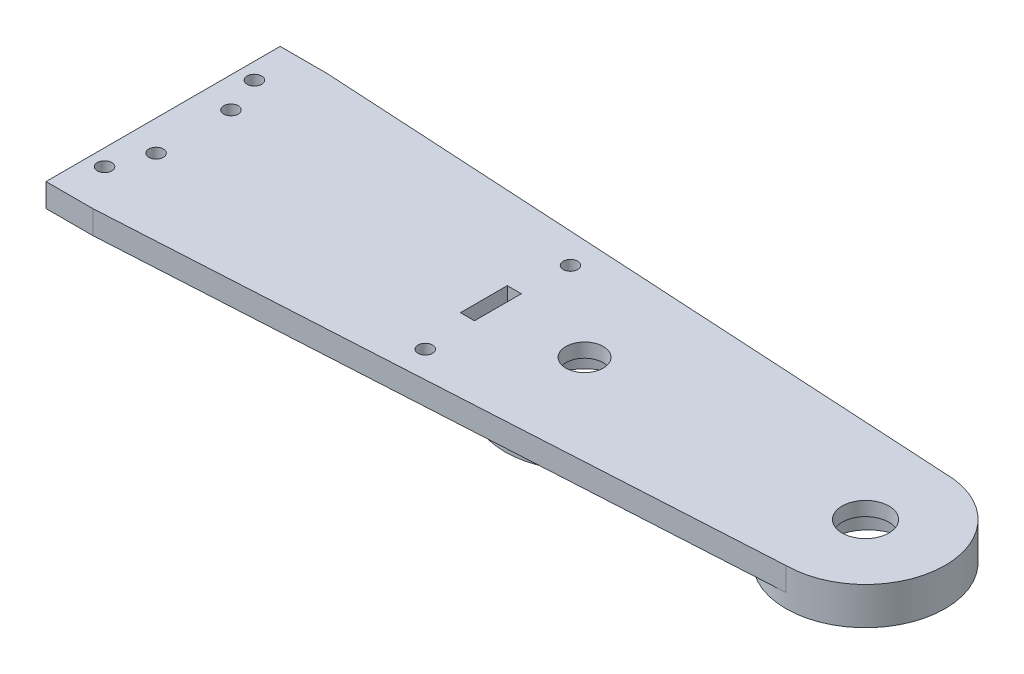
SolidWorks part; units mm, degrees
ref_plane "Front Plane" through (0, 0, 0) normal (0, 0, 1) x (1, 0, 0)
ref_plane "Top Plane" through (0, 0, 0) normal (0, 1, 0) x (1, 0, 0)
ref_plane "Right Plane" through (0, 0, 0) normal (1, 0, 0) x (0, 0, -1)
sketch "Sketch28" plane through (-32, 0, 0) normal (0, -1, 0) x (0, 0, 1)
  line L1 (0, -75) -> (0, -135) construction
  line L2 (-8, 8.5) -> (8, 8.5) construction
  line L3 (0, -75) -> (0, 15) construction
  line L8 (-25, 15) -> (25, 15)
  line L12 (25, 15) -> (25, 5)
  line L13 (-25, 15) -> (-25, 5)
  line L14 (-25, 5) -> (-17, -135)
  line L15 (17, -135) -> (25, 5)
  line L16 (-25, 5) -> (-25, 8.5) construction
  line L17 (-25, 8.5) -> (-8, 8.5) construction
  line L18 (-25, 15) -> (-25, 11.5) construction
  line L19 (-25, 11.5) -> (-16, 11.5) construction
  line L20 (-16, 11.5) -> (16, 11.5) construction
  line L21 (0, -75) -> (0, -56.5) construction
  line L22 (5, -56.5) -> (-5, -56.5)
  line L23 (-5, -56.5) -> (-5, -53.5)
  line L24 (-5, -53.5) -> (5, -53.5)
  line L25 (5, -53.5) -> (5, -56.5)
  line L26 (-5, -53.5) -> (-15.5, -53.5) construction
  line L27 (-15.5, -53.5) -> (-15.5, -56.5) construction
  line L28 (5, -53.5) -> (15.5, -53.5) construction
  line L29 (15.5, -53.5) -> (15.5, -56.5) construction
  circle A0 centre (0, -135) radius 5
  circle A3 centre (0, -75) radius 4
  arc A6 (17, -135) -> (-17, -135) centre (0, -135) cw
  circle A7 centre (8, 8.5) radius 1.55
  circle A8 centre (-8, 8.5) radius 1.55
  circle A9 centre (16, 11.5) radius 1.55
  circle A10 centre (-16, 11.5) radius 1.55
  circle A11 centre (-15.5, -56.5) radius 1.55
  circle A12 centre (15.5, -56.5) radius 1.55
  point P7 (0, 15)
  point P13 (0, 15)
  point P29 (0, -56.5)
extrude "Boss-Extrude10" add sketch "Sketch28" along normal blind 5
sketch "Sketch25" plane through (0, -5, 0) normal (0, -1, 0) x (0, 0, 1)
  circle A7 centre (0, -103) radius 17
extrude "Boss-Extrude8" add sketch "Sketch25" along normal blind 3
sketch "Sketch30" plane through (0, -5, 0) normal (0, -1, 0) x (0, 0, 1)
  circle A1 centre (0, -43) radius 17
extrude "Boss-Extrude11" add sketch "Sketch30" along normal blind 4
sketch "Sketch32" plane through (0, -9, 0) normal (0, -1, 0) x (1, 0, 0)
  circle A0 centre (43, 0) radius 9.7
extrude "Cut-Extrude3" cut sketch "Sketch32" against normal blind 6
sketch "Sketch33" plane through (0, -8, 0) normal (0, -1, 0) x (1, 0, 0)
  circle A0 centre (103, -0.5493) radius 8.2
extrude "Cut-Extrude4" cut sketch "Sketch33" against normal blind 5
